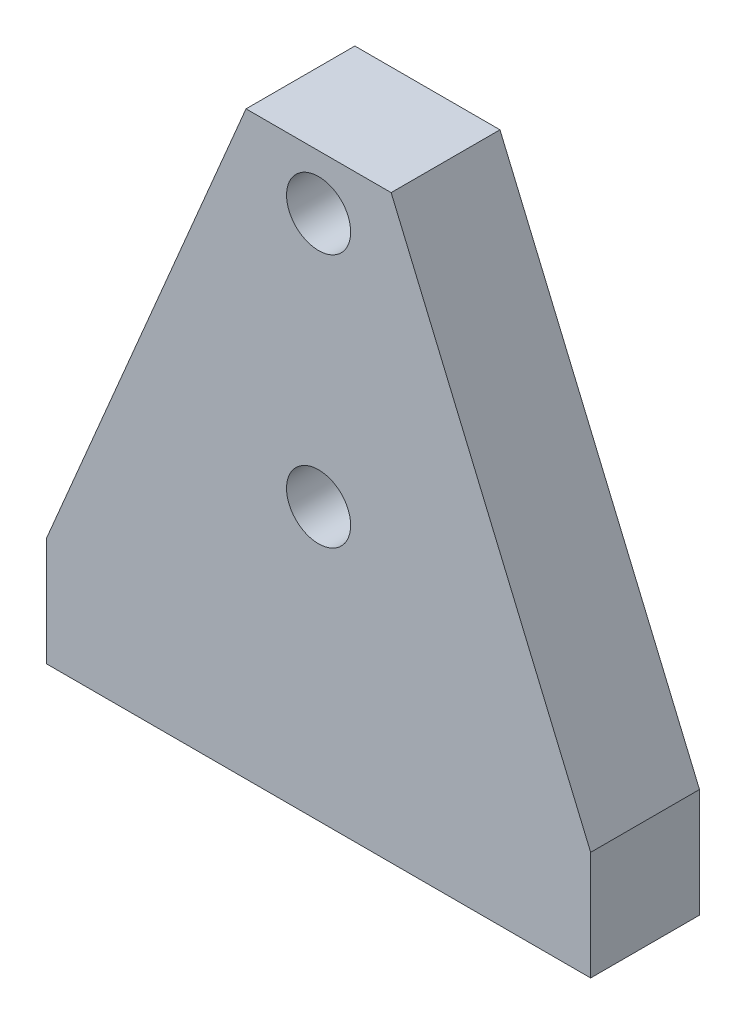
SolidWorks part; units mm, degrees
ref_plane "Front Plane" through (0, 0, 0) normal (0, 0, 1) x (1, 0, 0)
ref_plane "Top Plane" through (0, 0, 0) normal (0, 1, 0) x (1, 0, 0)
ref_plane "Right Plane" through (0, 0, 0) normal (1, 0, 0) x (0, 0, -1)
sketch "Sketch1" plane through (0, 0, 0) normal (0, 0, 1) x (1, 0, 0)
  line L0 (23.8125, -15.875) -> (6.35, 25.4)
  line L1 (-23.8125, 25.4) -> (23.8125, 25.4)
  line L2 (-23.8125, 25.4) -> (-23.8125, -25.4)
  line L3 (-23.8125, -25.4) -> (23.8125, -25.4)
  line L4 (23.8125, 25.4) -> (23.8125, -25.4)
  line L5 (-23.8125, 25.4) -> (23.8125, -25.4) construction
  line L6 (-23.8125, -25.4) -> (23.8125, 25.4) construction
  line L7 (-23.8125, -15.875) -> (-6.35, 25.4)
  line L9 (0, 0) -> (0, 13.061) construction
  point P0 (0, 0)
  dimension "D1" = 47.625
  dimension "D2" = 50.8
  dimension "D3" = 9.525
extrude "Boss-Extrude1" add sketch "Sketch1" along normal blind 9.525 contours L7 L2 L3 L4 L0 L1
hole_wizard "#10 Clearance Hole1" positions "Sketch3" profile "Sketch4" hole size "#10" standard "ANSI Inch" end condition through all
sketch "Sketch3" plane through (0, 0, 9.525) normal (0, 0, 1) x (1, 0, 0)
  line L0 (0, 20.6375) -> (0, -1.5875) construction
  line L4 (-23.8125, -15.875) -> (-23.8125, -25.4) construction
  line L5 (23.8125, -15.875) -> (23.8125, -25.4) construction
  circle A0 centre (0, 20.6375) radius 2.0193 construction
  circle A1 centre (0, -1.5875) radius 2.0193 construction
  point P0 (0, 20.6375)
  point P2 (0, -1.5875)
sketch "Sketch4" plane through (0, 20.6375, 9.525) normal (1, 0, 0) x (0, -1, 0)
  line L0 (0, 0) -> (0, 9.525)
  line L1 (0, 9.525) -> (2.8067, 9.525)
  line L2 (2.8067, 9.525) -> (2.8067, 0)
  line L5 (2.8067, 0) -> (0, 0)
  line L11 (0, -6.35) -> (0, 107.95) construction
  dimension "Thru Hole Dia." = 5.6134
  dimension "Thru Hole Depth" = 9.525
hole_wizard "M6x1.0 Tapped Hole1" positions "Sketch6" profile "Sketch5" tap size "M6x1.0" standard "ANSI Metric"
sketch "Sketch6" plane through (0, -25.4, 0) normal (0, -1, 0) x (-1, 0, 0)
  line L0 (13.9954, -4.7625) -> (-13.9954, -4.7625) construction
  line L2 (0, -4.7625) -> (0, 0) construction
  line L6 (23.8125, -9.525) -> (-23.8125, -9.525) construction
  line L7 (23.8125, 0) -> (-23.8125, 0) construction
  point P0 (13.9954, -4.7625)
  point P2 (-13.9954, -4.7625)
  dimension "D1" = 27.9908
sketch "Sketch5" plane through (-13.9954, -25.4, 4.7625) normal (1, 0, 0) x (0, 0, -1)
  line L0 (0, 0) -> (0, 13.0048)
  line L1 (0, 13.0048) -> (2.5, 13.0048)
  line L2 (2.5, 13.0048) -> (2.5, 0)
  line L5 (2.5, 0) -> (0, 0)
  line L10 (0, 13.0048) -> (-2.5, 13.0048) construction
  line L11 (0, -6.35) -> (0, 107.95) construction
  dimension "Tap Drill Dia." = 5
  dimension "Tap Drill Depth" = 13.0048
  dimension "Drill Angle" = 180
cosmetic thread "Hole Thread3" parameters "D1"=10.0076, "D2"=6
cosmetic thread "Hole Thread4" parameters "D1"=10.0076, "D2"=6
